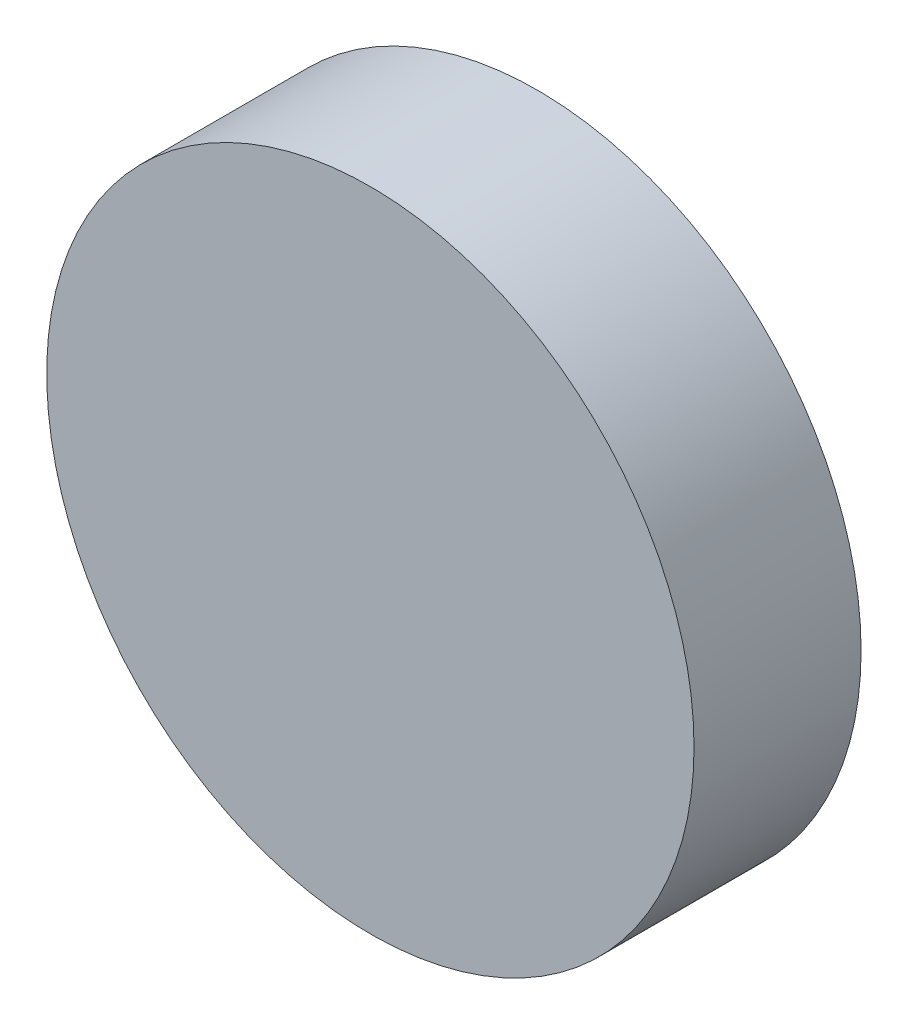
SolidWorks part; units mm, degrees
ref_plane "Front Plane" through (0, 0, 0) normal (0, 0, 1) x (1, 0, 0)
ref_plane "Top Plane" through (0, 0, 0) normal (0, 1, 0) x (1, 0, 0)
ref_plane "Right Plane" through (0, 0, 0) normal (1, 0, 0) x (0, 0, -1)
sketch "Sketch1" plane through (0, 0, 0) normal (0, 0, 1) x (1, 0, 0)
  circle A0 centre (0, 0) radius 7.75
  dimension "D1" = 15.5
extrude "Boss-Extrude1" add sketch "Sketch1" along normal blind 4
sketch "Sketch2" plane through (0, 0, 0) normal (1, 0, 0) x (0, 0, -1)
  line L0 (0, 0) -> (-2.96, 0) construction
  line L1 (0, 0) -> (0, 1.03) construction
  line L2 (0, 1.03) -> (-0.35, 1.03) construction
  line L3 (-0.35, 1.03) -> (-0.35, 0.86) construction
  line L4 (-0.35, 0.86) -> (-2.1, 0.86) construction
  line L5 (-0.4, 0.91) -> (-2.1, 0.91)
  line L6 (-0.4, 1.08) -> (-0.4, 0.91)
  line L7 (0.05, 1.08) -> (-0.4, 1.08)
  line L8 (0.05, -0.05) -> (0.05, 0) construction
  line L9 (0.05, -0.05) -> (-3.0086, -0.05) construction
  line L10 (-3.01, 0) -> (0.05, 0)
  line L11 (0.05, 0) -> (0.05, 1.08)
  line L12 (0.05, -0.05) -> (0.05, 1.08) construction
  arc A0 (-2.96, 0) -> (-2.1, 0.86) centre (-2.1, 0) cw construction
  arc A1 (-3.0086, -0.05) -> (-3.01, 0) centre (-2.1, 0) cw construction
  arc A2 (-3.01, 0) -> (-2.1, 0.91) centre (-2.1, 0) cw
  arc A3 (-3.0086, -0.05) -> (-2.1, 0.91) centre (-2.1, 0) cw construction
  point P1 (-3.01, -0.0054)
  point P9 (0.05, -0.0035)
  point P10 (-3.01, -0.0054)
  dimension "D1" = 0.35
  dimension "D2" = 2.61
  dimension "D3" = 0.86
  dimension "D4" = 1.03
  dimension "D5" = 0.05
revolve "Cut-Revolve1" cut sketch "Sketch2" angle 360 about L10
fillet "Fillet1" radius 0.05 1 edges at (0, -0.91, 0.4)
equation "\".5om\"=10"
